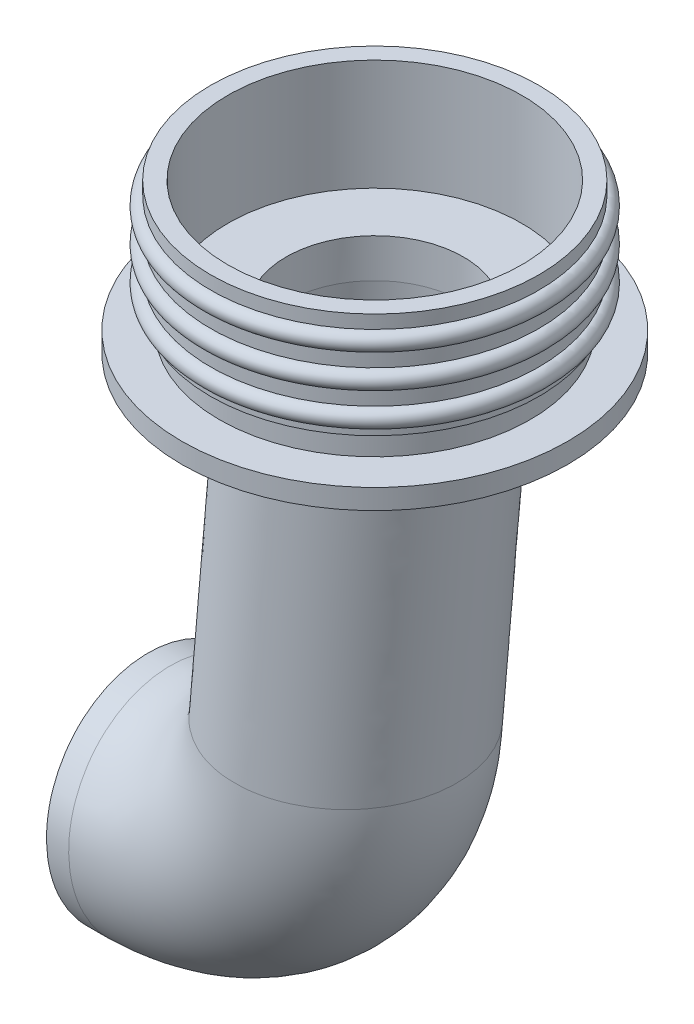
SolidWorks part; units mm, degrees
ref_plane "Front Plane" through (0, 0, 0) normal (0, 0, 1) x (1, 0, 0)
ref_plane "Top Plane" through (0, 0, 0) normal (0, 1, 0) x (1, 0, 0)
ref_plane "Right Plane" through (0, 0, 0) normal (1, 0, 0) x (0, 0, -1)
sketch "Sketch1" plane through (0, 0, 0) normal (0, 1, 0) x (1, 0, 0)
  circle A0 centre (0, 0) radius 17.4
  dimension "D1" = 34.8
extrude "Boss-Extrude1" add sketch "Sketch1" along normal blind 1.81
sketch "Sketch2" plane through (0, 1.81, 0) normal (0, 1, 0) x (1, 0, 0)
  circle A0 centre (0, 0) radius 14.02
  dimension "D1" = 28.04
extrude "Boss-Extrude2" add sketch "Sketch2" along normal blind 2.2
sketch "Sketch5" plane through (0, 4.01, 0) normal (0, 1, 0) x (1, 0, 0)
  circle A0 centre (0, 0) radius 14.8
  dimension "D1" = 29.6
extrude "Boss-Extrude3" add sketch "Sketch5" along normal blind 9.5
sketch "Sketch6" plane through (0, 13.51, 0) normal (0, 1, 0) x (1, 0, 0)
  circle A0 centre (0, 0) radius 13.25
  dimension "D1" = 26.5
extrude "Cut-Extrude1" cut sketch "Sketch6" against normal blind 10
sketch "Sketch7" plane through (0, 3.51, 0) normal (0, 1, 0) x (1, 0, 0)
  circle A0 centre (0, 0) radius 8
  dimension "D1" = 16
extrude "Cut-Extrude2" cut sketch "Sketch7" against normal through all
sketch "Sketch8" plane through (0, 0, 0) normal (1, 0, 0) x (0, 0, -1)
  line L0 (-14.8, 13.51) -> (-14.8, 4.01) construction
  line L1 (-14.8, 13.51) -> (-14.8, 4.01) construction
  line L2 (-14.8, 13.51) -> (-14.8, 4.01) construction
  line L3 (-14.8, 13.51) -> (-14.8, 4.01) construction
  line L4 (-14.8, 13.51) -> (-14.8, 4.01) construction
  line L5 (-14.8, 13.51) -> (-14.8, 4.01) construction
  line L6 (-14.8, 13.51) -> (-14.8, 4.01) construction
  line L7 (-14.8, 13.51) -> (-14.8, 4.01) construction
  line L8 (-14.8, 13.51) -> (-14.8, 4.01) construction
  line L9 (-14.8, 12.31) -> (-14.8, 10.71)
  line L10 (-14.8, 7.71) -> (-14.8, 9.31)
  line L11 (-14.8, 4.71) -> (-14.8, 6.31)
  arc A0 (-14.8, 9.31) -> (-14.8, 7.71) centre (-14.8, 8.51) ccw
  arc A1 (-14.8, 12.31) -> (-14.8, 10.71) centre (-14.8, 11.51) ccw
  arc A2 (-14.8, 6.31) -> (-14.8, 4.71) centre (-14.8, 5.51) ccw
  dimension "D4" = 0.8
  dimension "D1" = 2
  dimension "D2" = 3
  dimension "D3" = 3
ref_axis "Axis1" through (0, 3.51, 0) along (0, 1, 0)
revolve "Revolve1" add sketch "Sketch8" angle 360 about axis through (0, 3.51, 0) along (0, 1, 0)
sketch "Sketch9" plane through (0, 0, 0) normal (0, 0, 1) x (1, 0, 0)
  line L0 (0, 0) -> (-2.6147, -29.8858)
  line L1 (-17.4, 0) -> (17.4, 0) construction
  line L2 (-17.5576, -43.5785) -> (-19.5576, -43.5785)
  line L3 (-8, 0) -> (8, 0) construction
  arc A0 (-2.6147, -29.8858) -> (-17.5576, -43.5785) centre (-17.5576, -28.5785) cw
other "AlignGroup1" parameters "D2"=20.006, "D5"=10, "D1"=18.9578, "D3"=14.7818, "D4"=15, "D6"=5.1303, "D7"=2
sketch "Sketch10" plane through (0, 0, 0) normal (0, -1, 0) x (1, 0, 0)
  circle A0 centre (0, 0) radius 8
  circle A1 centre (0, 0) radius 10
  dimension "D1" = 2
sweep "Sweep1" add profiles "Sketch10" path "Sketch9"
ref_plane "Plane1" through (0, 0, 0) normal (0, 0, 1) x (1, 0, 0)
